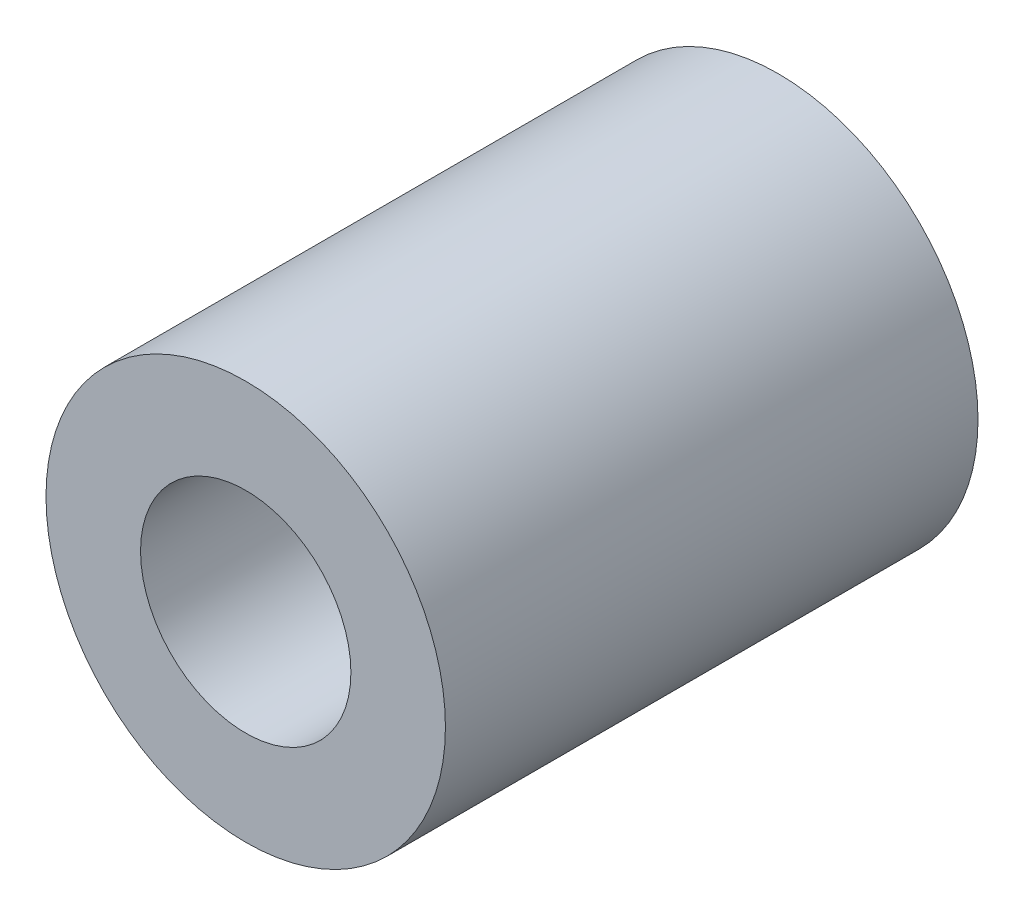
SolidWorks part; units mm, degrees
ref_plane "Front Plane" through (0, 0, 0) normal (0, 0, 1) x (1, 0, 0)
ref_plane "Top Plane" through (0, 0, 0) normal (0, 1, 0) x (1, 0, 0)
ref_plane "Right Plane" through (0, 0, 0) normal (1, 0, 0) x (0, 0, -1)
sketch "Sketch1" plane through (0, 0, 0) normal (0, 0, 1) x (1, 0, 0)
  circle A0 centre (0, 0) radius 19.05
  circle A1 centre (0, 0) radius 10.033
  dimension "D1" = 38.1
  dimension "D2" = 20.066
extrude "Extrude1" add sketch "Sketch1" along normal blind 50.8
